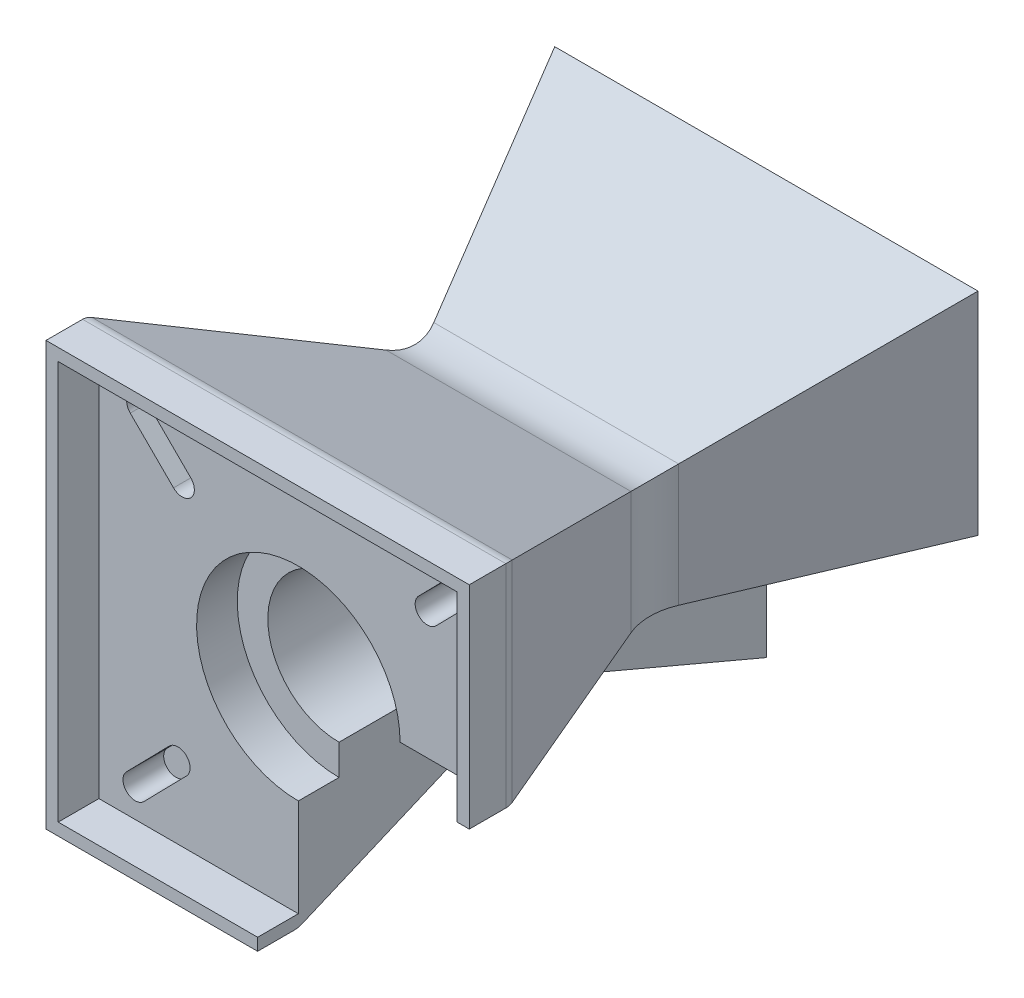
SolidWorks part; units mm, degrees
material "Cast Stainless Steel"
ref_plane "Front Plane" through (0, 0, 0) normal (0, 0, 1) x (1, 0, 0)
ref_plane "Top Plane" through (0, 0, 0) normal (0, 1, 0) x (1, 0, 0)
ref_plane "Right Plane" through (0, 0, 0) normal (1, 0, 0) x (0, 0, -1)
sketch "Sketch2" plane through (0, 0, 0) normal (0, 0, 1) x (1, 0, 0)
  line L0 (0, 0) -> (85.5616, 0) construction
  line L8 (0, 0) -> (104, 0)
  line L9 (0, 0) -> (0, 104)
  line L10 (0, 104) -> (104, 104)
  line L11 (104, 0) -> (104, 104)
  dimension "D1" = 104
  dimension "D2" = 104
extrude "Boss-Extrude2" add sketch "Sketch2" along normal blind 57.5 draft 23
mirror "Mirror19" about plane through (0, 0, 57.5) normal (0, 0, -1) of bodies 116
sketch "Sketch3" plane through (0, 0, 0) normal (0, 0, -1) x (-1, 0, 0)
  line L0 (-104, 104) -> (0, 104) construction
  line L1 (0, 104) -> (0, 0) construction
  circle A0 centre (-52, 52) radius 25
  dimension "D1" = 50
  dimension "D2" = 52
  dimension "D3" = 52
extrude "Cut-Extrude1" cut sketch "Sketch3" against normal through all
fillet "Fillet2" radius 15 1 edges at (24.4073, 52, 57.5)
fillet "Fillet3" radius 15 3 edges at (52, 24.4073, 57.5) (23.1634, 25.6512, 54.5695) (23.1119, 24.4073, 57.5)
fillet "Fillet4" radius 15 3 edges at (79.5927, 52, 57.5) (78.3488, 23.1634, 54.5695) (79.5927, 23.1119, 57.5)
fillet "Fillet5" radius 15 5 edges at (52, 79.5927, 57.5) (23.1634, 78.3488, 54.5695) (23.1119, 79.5927, 57.5) (80.8366, 78.3488, 54.5695) (80.8881, 79.5927, 57.5)
sketch "Sketch7" plane through (0, 0, 115) normal (0, 0, 1) x (1, 0, 0)
  circle A0 centre (52, 52) radius 25
  dimension "D1" = 50
extrude "Boss-Extrude3" add sketch "Sketch7" against normal blind 115
sketch "Sketch8" plane through (0, 0, 115) normal (0, 0, 1) x (1, 0, 0)
  line L0 (104, 104) -> (0, 104) construction
  line L1 (104, 0) -> (104, 104) construction
  circle A0 centre (52, 52) radius 17.5
  dimension "D1" = 35
  dimension "D2" = 52
  dimension "D3" = 52
extrude "Cut-Extrude2" cut sketch "Sketch8" against normal blind 10
sketch "Sketch9" plane through (0, 0, 115) normal (0, 0, 1) x (1, 0, 0)
  circle A0 centre (52, 52) radius 25
extrude "Cut-Extrude3" cut sketch "Sketch9" against normal blind 10
sketch "Sketch10" plane through (0, 0, 115) normal (0, 0, 1) x (1, 0, 0)
  circle A0 centre (52, 52) radius 17.5
  dimension "D1" = 35
extrude "Cut-Extrude4" cut sketch "Sketch10" against normal through all
sketch "Sketch11" plane through (0, 0, 115) normal (0, 0, 1) x (1, 0, 0)
  line L1 (52, 52) -> (104, 52)
  line L2 (52, 52) -> (52, 0)
  line L3 (52, 0) -> (104, 0)
  line L4 (104, 52) -> (104, 0)
extrude "Cut-Extrude5" cut sketch "Sketch11" against normal through all
sketch "Sketch12" plane through (0, 0, 115) normal (0, 0, 1) x (1, 0, 0)
  line L0 (52, 0) -> (0, 0)
  line L1 (0, 0) -> (0, 104)
  line L2 (0, 104) -> (104, 104)
  line L3 (104, 104) -> (104, 52)
  line L4 (104, 52) -> (101, 52)
  line L5 (104, 52) -> (77, 52) construction
  line L6 (101, 52) -> (101, 101)
  line L7 (101, 101) -> (3, 101)
  line L8 (3, 101) -> (3, 3)
  line L9 (3, 3) -> (52, 3)
  line L10 (52, 27) -> (52, 0) construction
  line L11 (52, 3) -> (52, 0)
  dimension "D1" = 3
  dimension "D2" = 3
  dimension "D3" = 3
  dimension "D4" = 3
extrude "Boss-Extrude4" add sketch "Sketch12" along normal blind 10
fillet "Fillet6" radius 5 1 edges at (26, 0, 115)
fillet "Fillet7" radius 5 3 edges at (0.2018, 0.228, 114.5246) (0, 0.0262, 115.506) (0, 52.0523, 115)
fillet "Fillet8" radius 5 3 edges at (0.228, 103.7982, 114.5246) (0.0262, 104, 115.506) (52.0523, 104, 115)
fillet "Fillet9" radius 5 3 edges at (104, 77.9477, 115) (103.7982, 103.772, 114.5246) (104, 103.9738, 115.506)
sketch "Sketch13" plane through (0, 0, 115) normal (0, 0, 1) x (1, 0, 0)
  line L0 (-0.0297, 103.7891) -> (105.1048, -0.8593) construction
  line L1 (1.0752, -1.0702) -> (104, 104) construction
  line L2 (12.8189, 91) -> (23.45, 80.418) construction
  line L3 (3, 101) -> (101, 101) construction
  line L4 (14.9353, 93.1262) -> (25.5664, 82.5442)
  line L5 (10.7025, 88.8738) -> (21.3336, 78.2918)
  line L6 (3, 3) -> (3, 101) construction
  line L7 (3, 3) -> (3, 101) construction
  line L8 (11.9193, 10) -> (22.416, 20.7154) construction
  line L9 (0, 0) -> (52, 0) construction
  line L10 (9.7762, 12.0993) -> (20.2729, 22.8148)
  line L11 (14.0624, 7.9007) -> (24.5591, 18.6161)
  line L12 (0, 104) -> (0, 0) construction
  line L13 (94.2042, 94) -> (83.7075, 83.2846) construction
  line L14 (104, 104) -> (0, 104) construction
  line L15 (96.3473, 91.9007) -> (85.8506, 81.1852)
  line L16 (92.0611, 96.0993) -> (81.5645, 85.3839)
  arc A0 (14.9353, 93.1262) -> (10.7025, 88.8738) centre (12.8189, 91) ccw
  arc A1 (21.3336, 78.2918) -> (25.5664, 82.5442) centre (23.45, 80.418) ccw
  arc A2 (77, 52) -> (52, 27) centre (52, 52) ccw construction
  arc A4 (9.7762, 12.0993) -> (14.0624, 7.9007) centre (11.9193, 10) ccw
  arc A5 (24.5591, 18.6161) -> (20.2729, 22.8148) centre (22.416, 20.7154) ccw
  arc A6 (96.3473, 91.9007) -> (92.0611, 96.0993) centre (94.2042, 94) ccw
  arc A7 (81.5645, 85.3839) -> (85.8506, 81.1852) centre (83.7075, 83.2846) ccw
  point P5 (52.5376, 51.4649)
  point P9 (18.1345, 85.709)
  point P11 (52.5376, 51.4649)
  point P29 (17.1676, 15.3577)
  point P34 (9.82, 7.8569)
  point P39 (88.9559, 88.6423)
  dimension "D1" = 3
  dimension "D2" = 10
  dimension "D3" = 40.2825
  dimension "D5" = 9.8189
  dimension "D6" = 3
  dimension "D8" = 10
  dimension "D10" = 15
  dimension "D11" = 3
  dimension "D12" = 10
  dimension "D4" = 45.133
  dimension "D7" = 15
  dimension "D9" = 9.82
extrude "Cut-Extrude6" cut sketch "Sketch13" against normal blind 10
sketch "Sketch14" plane through (0, 0, 0) normal (0, 0, -1) x (-1, 0, 0)
  circle A0 centre (-52, 52) radius 25
  dimension "D1" = 50
extrude "Cut-Extrude7" cut sketch "Sketch14" against normal blind 10
equation "\"a\"= 115"
equation "\"b\"= 104"
equation "\"c\"= 23deg"
